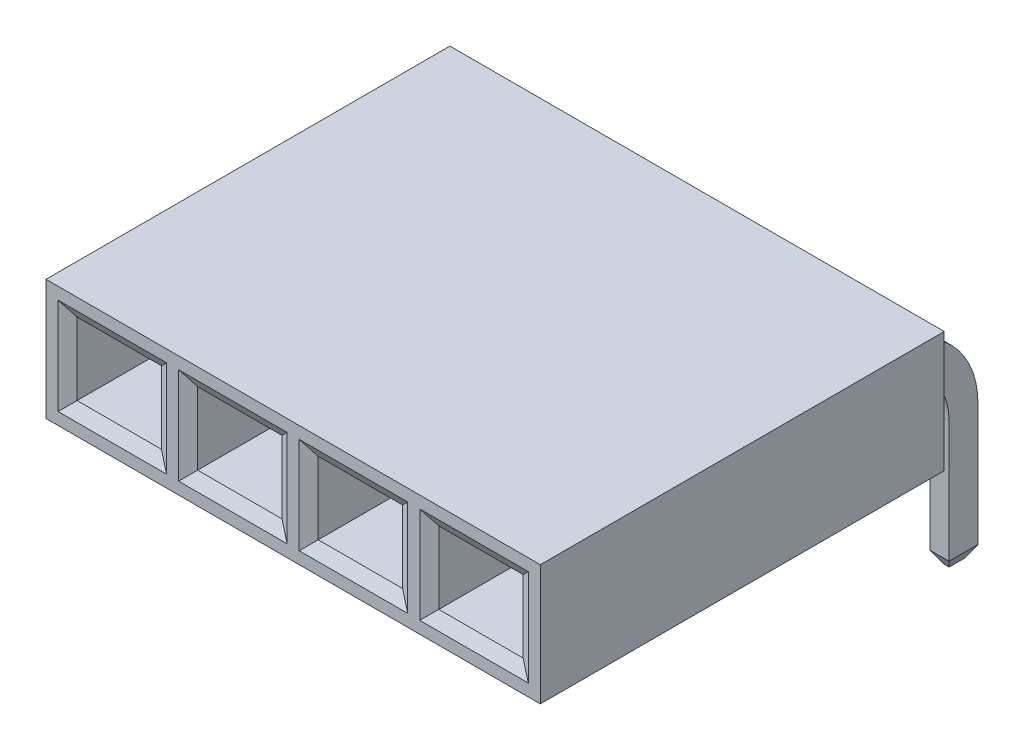
SolidWorks part; units mm, degrees
ref_plane "Front Plane" through (0, 0, 0) normal (0, 0, 1) x (1, 0, 0)
ref_plane "Top Plane" through (0, 0, 0) normal (0, 1, 0) x (1, 0, 0)
ref_plane "Right Plane" through (0, 0, 0) normal (1, 0, 0) x (0, 0, -1)
sketch "Sketch1" plane through (0, 0, 0) normal (0, 0, 1) x (1, 0, 0)
  line L1 (1.397, -1.27) -> (-1.397, -1.27)
  line L2 (1.397, -1.27) -> (1.397, 1.27)
  line L3 (1.397, 1.27) -> (-1.397, 1.27)
  line L4 (-1.397, -1.27) -> (-1.397, 1.27)
  line L5 (1.397, -1.27) -> (-1.397, 1.27) construction
  line L6 (1.397, 1.27) -> (-1.397, -1.27) construction
  point P0 (0, 0)
  dimension "D1" = 2.54
  dimension "D2" = 2.794
extrude "Boss-Extrude1" add sketch "Sketch1" along normal mid plane 8.509
sketch "Sketch2" plane through (0, 0, 0) normal (1, 0, 0) x (0, 0, -1)
  line L0 (5.8547, -4.4196) -> (5.8547, -1.6002)
  line L1 (4.2545, -1.27) -> (4.2545, 1.27) construction
  line L2 (4.2545, 0) -> (12.9748, 0) construction
  line L3 (-4.2545, -1.27) -> (4.2545, -1.27) construction
  arc A0 (4.2545, 0) -> (5.8547, -1.6002) centre (4.2545, -1.6002) cw
  dimension "D1" = 1.6002
  dimension "D2" = 3.1496
sketch "Sketch3" plane through (0, 0, -4.2545) normal (0, 0, -1) x (-1, 0, 0)
  line L1 (-0.2032, -0.3048) -> (0.2032, -0.3048)
  line L2 (-0.2032, -0.3048) -> (-0.2032, 0.3048)
  line L3 (-0.2032, 0.3048) -> (0.2032, 0.3048)
  line L4 (0.2032, -0.3048) -> (0.2032, 0.3048)
  line L5 (-0.2032, -0.3048) -> (0.2032, 0.3048) construction
  line L6 (-0.2032, 0.3048) -> (0.2032, -0.3048) construction
  point P0 (0, 0)
  dimension "D1" = 0.6096
  dimension "D2" = 0.4064
sweep "Sweep1" add profiles "Sketch3" path "Sketch2"
chamfer "Chamfer1" distance 0.254 angle 30 4 edges at (0, -4.4196, -5.5499) (-0.2032, -4.4196, -5.8547) (0, -4.4196, -6.1595) (0.2032, -4.4196, -5.8547)
sketch "Sketch4" plane through (0, 0, 4.2545) normal (0, 0, 1) x (1, 0, 0)
  line L0 (0.889, 0) -> (1.397, 0) construction
  line L1 (-0.889, -0.762) -> (0.889, -0.762)
  line L2 (-0.889, -0.762) -> (-0.889, 0.762)
  line L3 (-0.889, 0.762) -> (0.889, 0.762)
  line L4 (0.889, -0.762) -> (0.889, 0.762)
  line L5 (-0.889, -0.762) -> (0.889, 0.762) construction
  line L6 (-0.889, 0.762) -> (0.889, -0.762) construction
  line L7 (1.397, -1.27) -> (1.397, 1.27) construction
  line L8 (0, 0.762) -> (0, 1.27) construction
  line L9 (1.397, 1.27) -> (-1.397, 1.27) construction
  point P0 (0, 0)
  dimension "D1" = 0.508
extrude "Cut-Extrude1" cut sketch "Sketch4" against normal blind 6.35
chamfer "Chamfer2" distance 0.254 angle 30 4 edges at (-0.889, 0, 4.2545) (0, 0.762, 4.2545) (0.889, 0, 4.2545) (0, -0.762, 4.2545)
pattern_linear "LPattern1" count 4 spacing 2.54 along (1, 0, 0) of "Boss-Extrude1", "Sweep1", "Cut-Extrude1", "Chamfer1", "Chamfer2"
ref_point "Point1"
ref_point "Point2"
